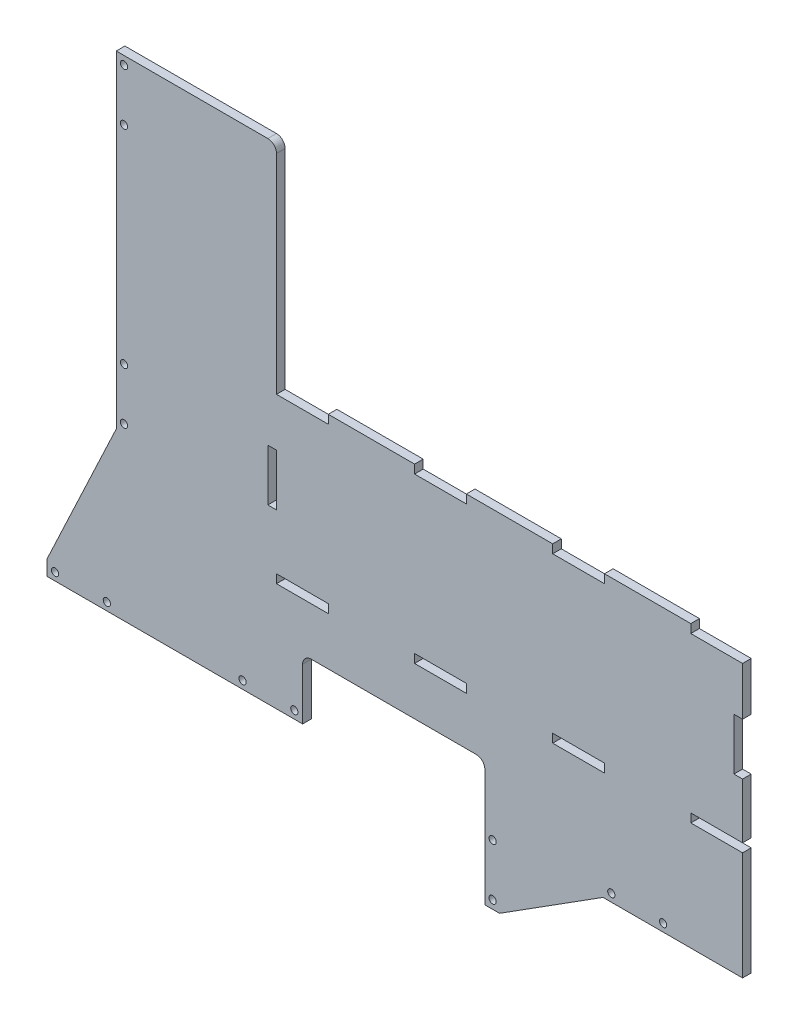
SolidWorks part; units mm, degrees
ref_plane "Front Plane" through (0, 0, 0) normal (0, 0, 1) x (1, 0, 0)
ref_plane "Top Plane" through (0, 0, 0) normal (0, 1, 0) x (1, 0, 0)
ref_plane "Right Plane" through (0, 0, 0) normal (1, 0, 0) x (0, 0, -1)
sketch "Sketch1" plane through (0, 0, 0) normal (0, 0, 1) x (1, 0, 0)
  line L72 (95.7, 370.8308) -> (87.2, 370.8308)
  line L73 (87.2, 370.8308) -> (87.2, 331.2308)
  line L77 (369.1692, 87.2) -> (408.7692, 87.2)
  line L81 (300.7, 88.8368) -> (300.7, 49.2368)
  line L82 (300.7, 49.2368) -> (309.2, 49.2368)
  line L85 (155.5572, 87.2) -> (195.1572, 87.2)
  line L88 (46.9632, 95.7) -> (46.9632, 87.2)
  line L89 (46.9632, 87.2) -> (86.5632, 87.2)
  line L93 (87.2, 220.8308) -> (87.2, 181.2308)
  line L96 (46.9632, 95.7) -> (87.2, 181.2308)
  line L97 (87.2, 220.8308) -> (87.2, 331.2308)
  line L98 (95.7, 370.8308) -> (175, 370.8308)
  line L99 (180, 365.8308) -> (180, 245)
  line L100 (210, 250) -> (260, 250)
  line L101 (450, 245) -> (450, 217)
  line L102 (450, 87.2) -> (408.7692, 87.2)
  line L103 (0, 0) -> (263.9074, 0) construction
  line L104 (0, 0) -> (0, 21.7019) construction
  line L105 (369.1692, 87.2) -> (309.2, 49.2368)
  line L107 (155.5572, 87.2) -> (86.5632, 87.2)
  line L108 (195.1572, 87.2) -> (195.1572, 117.2)
  line L109 (200.1572, 122.2) -> (295.7, 122.2)
  line L110 (300.7, 117.2) -> (300.7, 88.8368)
  line L111 (290, 250) -> (340, 250)
  line L114 (180, 245) -> (210, 245)
  line L115 (210, 250) -> (210, 245)
  line L118 (450, 245) -> (420, 245)
  line L119 (420, 250) -> (420, 245)
  line L121 (260, 250) -> (260, 245)
  line L122 (260, 245) -> (290, 245)
  line L123 (290, 250) -> (290, 245)
  line L125 (340, 250) -> (340, 245)
  line L126 (340, 245) -> (370, 245)
  line L127 (370, 250) -> (370, 245)
  line L128 (370, 250) -> (420, 250)
  line L129 (185.4558, 150) -> (277.9701, 150) construction
  line L130 (450, 187) -> (450, 87.2)
  line L131 (180, 150) -> (210, 150)
  line L132 (180, 150) -> (180, 155)
  line L133 (180, 155) -> (210, 155)
  line L134 (210, 150) -> (210, 155)
  line L135 (260, 155) -> (290, 155)
  line L136 (260, 155) -> (260, 150)
  line L137 (260, 150) -> (290, 150)
  line L138 (290, 155) -> (290, 150)
  line L139 (340, 150) -> (370, 150)
  line L140 (340, 150) -> (340, 155)
  line L141 (340, 155) -> (370, 155)
  line L142 (370, 150) -> (370, 155)
  line L143 (420, 150) -> (450, 150)
  line L144 (420, 150) -> (420, 155)
  line L145 (420, 155) -> (450, 155)
  line L146 (450, 150) -> (450, 155)
  line L147 (450, 217) -> (445, 217)
  line L149 (450, 187) -> (445, 187)
  line L150 (445, 217) -> (445, 187)
  line L152 (175, 217) -> (180, 217)
  line L153 (175, 217) -> (175, 187)
  line L154 (175, 187) -> (180, 187)
  line L155 (180, 217) -> (180, 187)
  circle A1 centre (91.7, 366.0308) radius 2.1
  circle A2 centre (91.7, 336.0308) radius 2.1
  circle A11 centre (403.9692, 91.7) radius 2.1
  circle A12 centre (373.9692, 91.7) radius 2.1
  circle A13 centre (305.2, 54.0368) radius 2.1
  circle A14 centre (305.2, 84.0368) radius 2.1
  circle A15 centre (190.3572, 91.7) radius 2.1
  circle A16 centre (160.3572, 91.7) radius 2.1
  circle A17 centre (51.7632, 91.7) radius 2.1
  circle A18 centre (81.7632, 91.7) radius 2.1
  circle A21 centre (91.7, 186.0308) radius 2.1
  circle A22 centre (91.7, 216.0308) radius 2.1
  arc A23 (175, 370.8308) -> (180, 365.8308) centre (175, 365.8308) cw
  arc A24 (295.7, 122.2) -> (300.7, 117.2) centre (295.7, 117.2) cw
  arc A25 (195.1572, 117.2) -> (200.1572, 122.2) centre (200.1572, 117.2) cw
  point P93 (161.5286, 212.8448)
  dimension "D1" = 450
  dimension "D2" = 35
  dimension "D5" = 5
  dimension "D30" = 5
  dimension "D3" = 250
  dimension "D4" = 180
  dimension "D6" = 30
  dimension "D7" = 5
  dimension "D8" = 30
  dimension "D9" = 5
  dimension "D10" = 30
  dimension "D11" = 5
  dimension "D12" = 5
  dimension "D13" = 30
  dimension "D14" = 50
  dimension "D15" = 50
  dimension "D16" = 150
  dimension "D17" = 30
  dimension "D18" = 5
  dimension "D19" = 30
  dimension "D20" = 5
  dimension "D21" = 5
  dimension "D22" = 30
  dimension "D23" = 50
  dimension "D24" = 50
  dimension "D25" = 30
  dimension "D26" = 5
  dimension "D27" = 30
  dimension "D28" = 28
  dimension "D29" = 5
  dimension "D31" = 30
  dimension "D32" = 5
extrude "Boss-Extrude1" add sketch "Sketch1" along normal blind 5 contours A23 L98 L72 L73 L97 L93 L96 L88 L89 L107 L85 L108 L109 L110 L81 L82 L105 L77 L102 L130 L143 L144 L145 L149 L150 L147 L101 L118 L119 L128 L127 L126 L125 L111 L123 L122 L121 L100 L115 L114 L99 A22 A21 A18 A17
